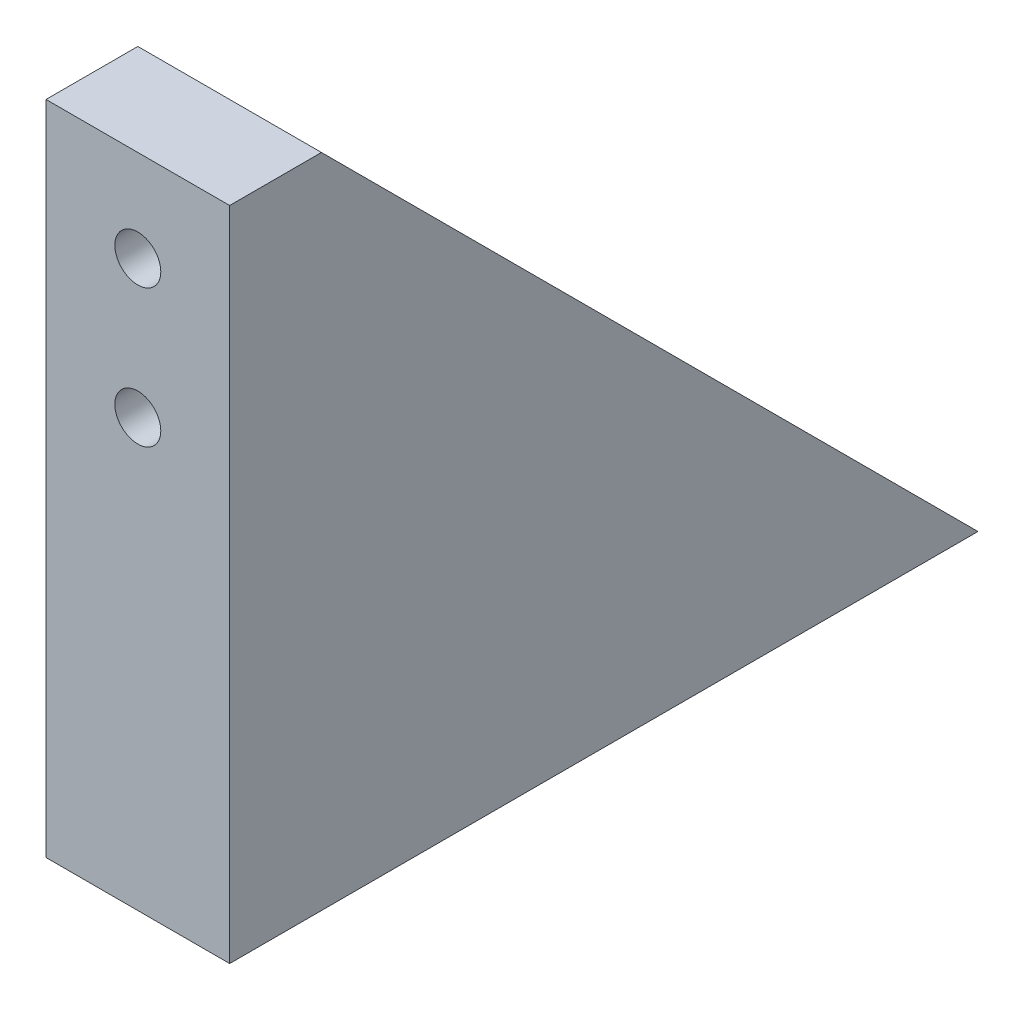
SolidWorks part; units mm, degrees
material "PLA"
ref_plane "Front Plane" through (0, 0, 0) normal (0, 0, 1) x (1, 0, 0)
ref_plane "Top Plane" through (0, 0, 0) normal (0, 1, 0) x (1, 0, 0)
ref_plane "Right Plane" through (0, 0, 0) normal (1, 0, 0) x (0, 0, -1)
sketch "Sketch1" plane through (0, 0, 0) normal (0, 0, 1) x (1, 0, 0)
  line L0 (0, 25.75) -> (0, 10.75) construction
  line L1 (-10, -35.75) -> (10, -35.75)
  line L2 (-10, -35.75) -> (-10, 35.75)
  line L3 (-10, 35.75) -> (10, 35.75)
  line L4 (10, -35.75) -> (10, 35.75)
  line L5 (-10, -35.75) -> (10, 35.75) construction
  line L6 (-10, 35.75) -> (10, -35.75) construction
  circle A0 centre (0, 25.75) radius 2.5
  circle A1 centre (0, 10.75) radius 2.5
  point P0 (0, 0)
  point P10 (0, 18.25)
  point P11 (0.079, 18.5589)
  point P12 (0, 26.0916)
  dimension "D2" = 5
  dimension "D1" = 54
  dimension "D3" = 15
  dimension "D4" = 20
  dimension "D5" = 10
extrude "Boss-Extrude1" add sketch "Sketch1" along normal mid plane 10
sketch "Sketch2" plane through (10, 0, 0) normal (1, 0, 0) x (0, 0, -1)
  line L0 (5, 35.75) -> (5, -35.75)
  line L1 (5, -35.75) -> (76.5, -35.75)
  line L2 (76.5, -35.75) -> (5, 35.75)
  dimension "D1" = 45
extrude "Boss-Extrude2" add sketch "Sketch2" against normal through all
sketch "Sketch3" plane through (0, 0, -5) normal (0, 0, 1) x (1, 0, 0)
  circle A0 centre (0, 25.75) radius 3.5
  circle A1 centre (0, 10.75) radius 3.5
  dimension "D1" = 7
extrude "Cut-Extrude1" cut sketch "Sketch3" against normal up to next
sketch "Sketch4" plane through (0, -35.75, 0) normal (0, -1, 0) x (1, 0, 0)
  line L1 (-10, 5) -> (10, 5) construction
  circle A0 centre (0, -5) radius 1.5
  circle A1 centre (0, -45) radius 1.5
  point P4 (0, 0)
  point P6 (2.2341, -47.4491)
  point P7 (0, -44.0939)
  point P8 (0, -5.1368)
  dimension "D1" = 3
  dimension "D2" = 10
  dimension "D3" = 40
extrude "Cut-Extrude2" cut sketch "Sketch4" against normal blind 10
